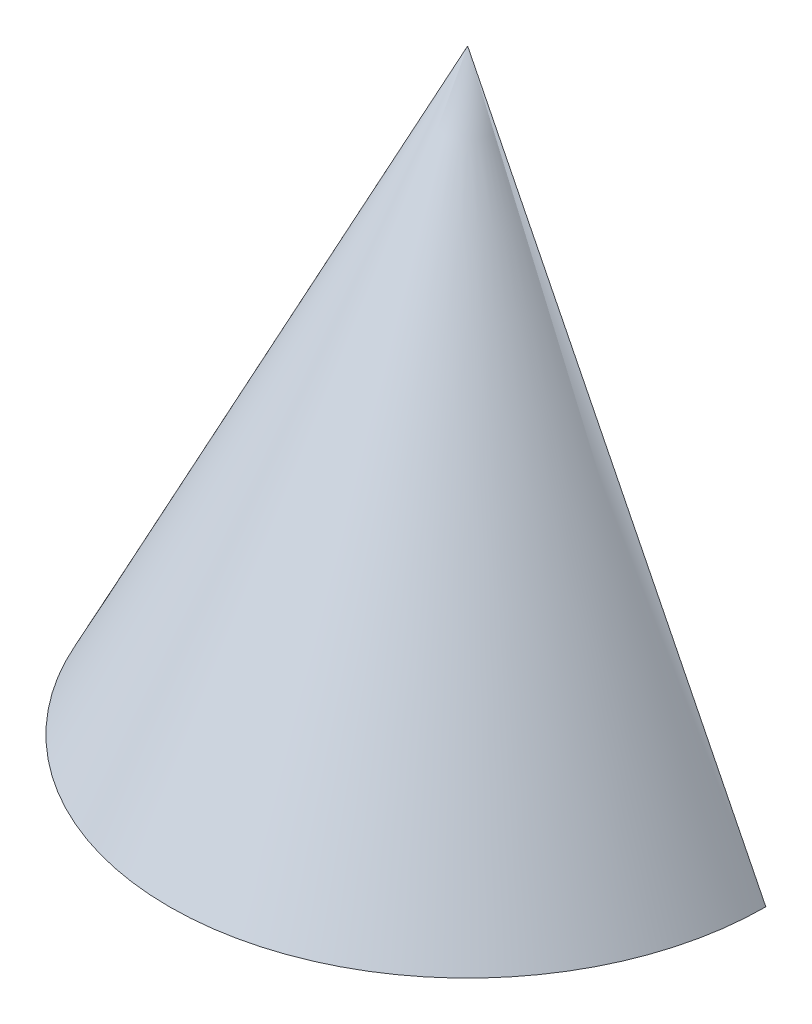
SolidWorks part; units mm, degrees
ref_plane "Front Plane" through (0, 0, 0) normal (0, 0, 1) x (1, 0, 0)
ref_plane "Top Plane" through (0, 0, 0) normal (0, 1, 0) x (1, 0, 0)
ref_plane "Right Plane" through (0, 0, 0) normal (1, 0, 0) x (0, 0, -1)
sketch "Sketch1" plane through (0, 0, 0) normal (0, 0, 1) x (1, 0, 0)
  line L0 (0, 0) -> (45, 0)
  line L1 (45, 0) -> (0, 90)
  line L2 (0, 90) -> (0, 0)
  dimension "D1" = 90
  dimension "D2" = 45
revolve "Revolve1" add sketch "Sketch1" angle 180 about L2
sketch "Sketch2" plane through (0, 0, 0) normal (0, 0, -1) x (-1, 0, 0)
  line L0 (0, 0) -> (0, 85)
  line L1 (0, 85) -> (-42.5092, 0)
  line L2 (-45, 0) -> (45, 0) construction
  line L3 (-42.5092, 0) -> (0, 0)
  line L4 (45, 0) -> (0, 90) construction
  dimension "D1" = 63.435
  dimension "D2" = 63.43
  dimension "D3" = 85
revolve "Cut-Revolve1" cut sketch "Sketch2" angle 360 about L0
sketch "Sketch3" plane through (0, 0, 0) normal (0, -1, 0) x (-1, 0, 0)
  line L0 (42.5092, 0) -> (-42.5092, 0)
  arc A0 (-42.5092, 0) -> (42.5092, 0) centre (0, 0) ccw
extrude "Boss-Extrude1" add sketch "Sketch3" against normal blind 2.5
ref_plane "Plane1" through (0, 10, 0) normal (0, -1, 0) x (-1, 0, 0)
sketch "Sketch4" plane through (0, 10, 0) normal (0, -1, 0) x (-1, 0, 0)
  line L0 (-38.2213, 0) -> (38.2213, 0)
  arc A0 (-38.2213, 0) -> (38.2213, 0) centre (0, 0) ccw
extrude "Boss-Extrude2" add sketch "Sketch4" against normal blind 2.5
ref_plane "Plane2" through (0, 20, 0) normal (0, -1, 0) x (-1, 0, 0)
sketch "Sketch5" plane through (0, 20, 0) normal (0, -1, 0) x (-1, 0, 0)
  line L0 (-33.5, 0) -> (33.5, 0)
  arc A0 (-33.5, 0) -> (33.5, 0) centre (0, 0) ccw
  dimension "D1" = 67
extrude "Boss-Extrude3" add sketch "Sketch5" against normal blind 2.5
